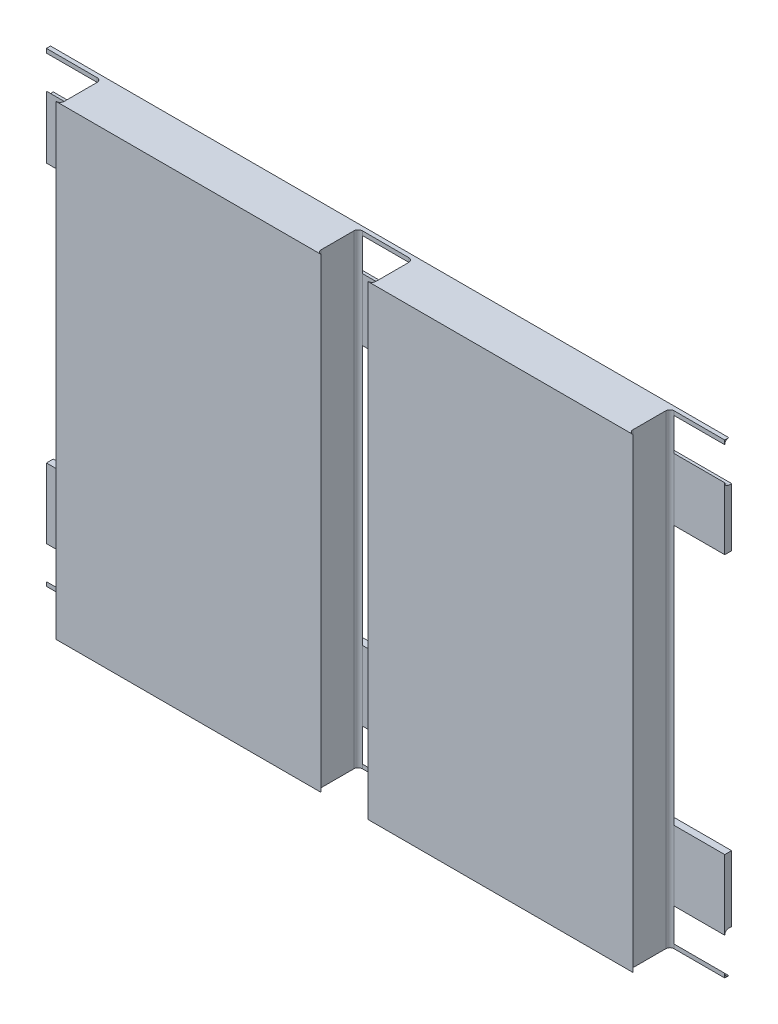
SolidWorks part; units mm, degrees
material "FLUECO75"
ref_plane "Front Plane" through (0, 0, 0) normal (0, 0, 1) x (1, 0, 0)
ref_plane "Top Plane" through (0, 0, 0) normal (0, 1, 0) x (1, 0, 0)
ref_plane "Right Plane" through (0, 0, 0) normal (1, 0, 0) x (0, 0, -1)
sketch "Sketch1" plane through (0, 0, 0) normal (0, 0, 1) x (1, 0, 0)
  line L0 (495, -680) -> (495, 0) construction
  line L1 (-495, 0) -> (495, 0)
  line L2 (-495, 0) -> (-495, -680)
  line L3 (-495, -680) -> (495, -680)
  line L4 (495, 0) -> (495, -680)
  line L5 (-495, -680) -> (-495, 0) construction
  line L6 (-495, 0) -> (495, 0) construction
  line L7 (-495, -680) -> (495, -680) construction
extrude "Boss-Extrude1" add sketch "Sketch1" against normal up to surface (70 mm away)
sketch "Sketch2" plane through (0, 0, -70) normal (0, 0, -1) x (-1, 0, 0)
  line L0 (-495, -680) -> (-495, 0) construction
  line L1 (-495, -524) -> (495, -524)
  line L2 (-495, -524) -> (-495, -145)
  line L3 (-495, -145) -> (495, -145)
  line L4 (495, -524) -> (495, -145)
  line L5 (495, 0) -> (495, -680) construction
  line L10 (-489, -524) -> (489, -524)
  line L11 (489, -524) -> (489, -145)
  line L12 (489, -145) -> (-489, -145)
  line L13 (-489, -145) -> (-489, -524)
  line L14 (-489, -524) -> (489, -524)
  line L15 (489, -524) -> (489, -145)
  line L16 (489, -145) -> (-489, -145)
  line L17 (-489, -145) -> (-489, -524)
  dimension "D1" = 0
extrude "Cut-Extrude1" cut sketch "Sketch2" against normal blind 10 contours L2 L1 L4 L3
sketch "Sketch3" plane through (-495, 0, 0) normal (-1, 0, 0) x (0, 0, 1)
  line L0 (-134, -680) -> (-66, -680) construction
  line L1 (-60, -674) -> (-60, -626) construction
  line L2 (-66, -620) -> (-134, -620) construction
  line L3 (-140, -626) -> (-140, -674) construction
  line L5 (-134, -60) -> (-66, -60) construction
  line L6 (-60, -54) -> (-60, -6) construction
  line L7 (-66, 0) -> (-134, 0) construction
  line L13 (-140, -6) -> (-140, -54) construction
  line L14 (-134, -680) -> (-66, -680)
  line L15 (-60, -674) -> (-60, -626)
  line L20 (-66, -620) -> (-134, -620)
  line L21 (-140, -626) -> (-140, -674)
  line L22 (-134, -60) -> (-66, -60)
  line L23 (-60, -54) -> (-60, -6)
  line L24 (-66, 0) -> (-134, 0)
  line L25 (-140, -6) -> (-140, -54)
  arc A0 (-140, -674) -> (-134, -680) centre (-134, -674) ccw construction
  arc A1 (-66, -680) -> (-60, -674) centre (-66, -674) ccw construction
  arc A2 (-60, -626) -> (-66, -620) centre (-66, -626) ccw construction
  arc A3 (-134, -620) -> (-140, -626) centre (-134, -626) ccw construction
  arc A20 (-140, -54) -> (-134, -60) centre (-134, -54) ccw construction
  arc A21 (-66, -60) -> (-60, -54) centre (-66, -54) ccw construction
  arc A22 (-60, -6) -> (-66, 0) centre (-66, -6) ccw construction
  arc A23 (-134, 0) -> (-140, -6) centre (-134, -6) ccw construction
  arc A24 (-140, -674) -> (-134, -680) centre (-134, -674) ccw
  arc A25 (-66, -680) -> (-60, -674) centre (-66, -674) ccw
  arc A26 (-60, -626) -> (-66, -620) centre (-66, -626) ccw
  arc A27 (-134, -620) -> (-140, -626) centre (-134, -626) ccw
  arc A28 (-140, -54) -> (-134, -60) centre (-134, -54) ccw
  arc A29 (-66, -60) -> (-60, -54) centre (-66, -54) ccw
  arc A30 (-60, -6) -> (-66, 0) centre (-66, -6) ccw
  arc A31 (-134, 0) -> (-140, -6) centre (-134, -6) ccw
extrude "Cut-Extrude2" cut sketch "Sketch3" against normal through all contours A24 L14 A25 L15 A26 L20 A27 L21 | A28 L22 A29 L23 A30 L24 A31 L25
sketch "Sketch5" plane through (0, -680, 0) normal (0, -1, 0) x (1, 0, 0)
  line L0 (-489, -60) -> (-421, -60) construction
  line L1 (-415, -54) -> (-415, -6) construction
  line L2 (-421, 0) -> (-489, 0) construction
  line L3 (-495, -6) -> (-495, -54) construction
  line L4 (-34, -60) -> (34, -60) construction
  line L5 (40, -54) -> (40, -6) construction
  line L6 (34, 0) -> (-34, 0) construction
  line L7 (-40, -6) -> (-40, -54) construction
  line L8 (421, -60) -> (489, -60) construction
  line L9 (495, -54) -> (495, -6) construction
  line L10 (489, 0) -> (421, 0) construction
  line L11 (415, -6) -> (415, -54) construction
  line L12 (-489, -60) -> (-421, -60)
  line L13 (-415, -54) -> (-415, -6)
  line L14 (-421, 0) -> (-489, 0)
  line L15 (-495, -6) -> (-495, -54)
  line L16 (-34, -60) -> (34, -60)
  line L17 (40, -54) -> (40, -6)
  line L18 (34, 0) -> (-34, 0)
  line L19 (-40, -6) -> (-40, -54)
  line L20 (421, -60) -> (489, -60)
  line L21 (495, -54) -> (495, -6)
  line L22 (489, 0) -> (421, 0)
  line L23 (415, -6) -> (415, -54)
  line L25 (489, -60) -> (495, -60)
  line L26 (489, -60) -> (489, 0)
  line L27 (489, 0) -> (495, 0)
  line L28 (495, -60) -> (495, 0)
  line L29 (-489, -60) -> (-495, -60)
  line L30 (-489, -60) -> (-489, 0)
  line L31 (-489, 0) -> (-495, 0)
  line L32 (-495, -60) -> (-495, 0)
  arc A0 (-495, -54) -> (-489, -60) centre (-489, -54) ccw construction
  arc A1 (-421, -60) -> (-415, -54) centre (-421, -54) ccw construction
  arc A2 (-415, -6) -> (-421, 0) centre (-421, -6) ccw construction
  arc A3 (-489, 0) -> (-495, -6) centre (-489, -6) ccw construction
  arc A4 (-40, -54) -> (-34, -60) centre (-34, -54) ccw construction
  arc A5 (34, -60) -> (40, -54) centre (34, -54) ccw construction
  arc A6 (40, -6) -> (34, 0) centre (34, -6) ccw construction
  arc A7 (-34, 0) -> (-40, -6) centre (-34, -6) ccw construction
  arc A8 (415, -54) -> (421, -60) centre (421, -54) ccw construction
  arc A9 (489, -60) -> (495, -54) centre (489, -54) ccw construction
  arc A10 (495, -6) -> (489, 0) centre (489, -6) ccw construction
  arc A11 (421, 0) -> (415, -6) centre (421, -6) ccw construction
  arc A12 (-495, -54) -> (-489, -60) centre (-489, -54) ccw
  arc A13 (-421, -60) -> (-415, -54) centre (-421, -54) ccw
  arc A14 (-415, -6) -> (-421, 0) centre (-421, -6) ccw
  arc A15 (-489, 0) -> (-495, -6) centre (-489, -6) ccw
  arc A16 (-40, -54) -> (-34, -60) centre (-34, -54) ccw
  arc A17 (34, -60) -> (40, -54) centre (34, -54) ccw
  arc A18 (40, -6) -> (34, 0) centre (34, -6) ccw
  arc A19 (-34, 0) -> (-40, -6) centre (-34, -6) ccw
  arc A20 (415, -54) -> (421, -60) centre (421, -54) ccw
  arc A21 (489, -60) -> (495, -54) centre (489, -54) ccw
  arc A22 (495, -6) -> (489, 0) centre (489, -6) ccw
  arc A23 (421, 0) -> (415, -6) centre (421, -6) ccw
  line M10 (495, -66) -> (495, 0)
  line M11 (495, 0) -> (-495, 0)
  line M12 (-495, 0) -> (-495, -66)
extrude "Cut-Extrude4" cut sketch "Sketch5" against normal through all contours A22 L26 A21 M10 | A23 L23 A20 L20 L26 M11 | A19 L19 A16 L16 A17 L17 A18 M11 | L13 A14 L30 L12 A13 M11 | L30 A15 A12 M12 | A12 L29 M12 | A15 M11 M12 | A22 M10 M11 | A21 L25 M10
